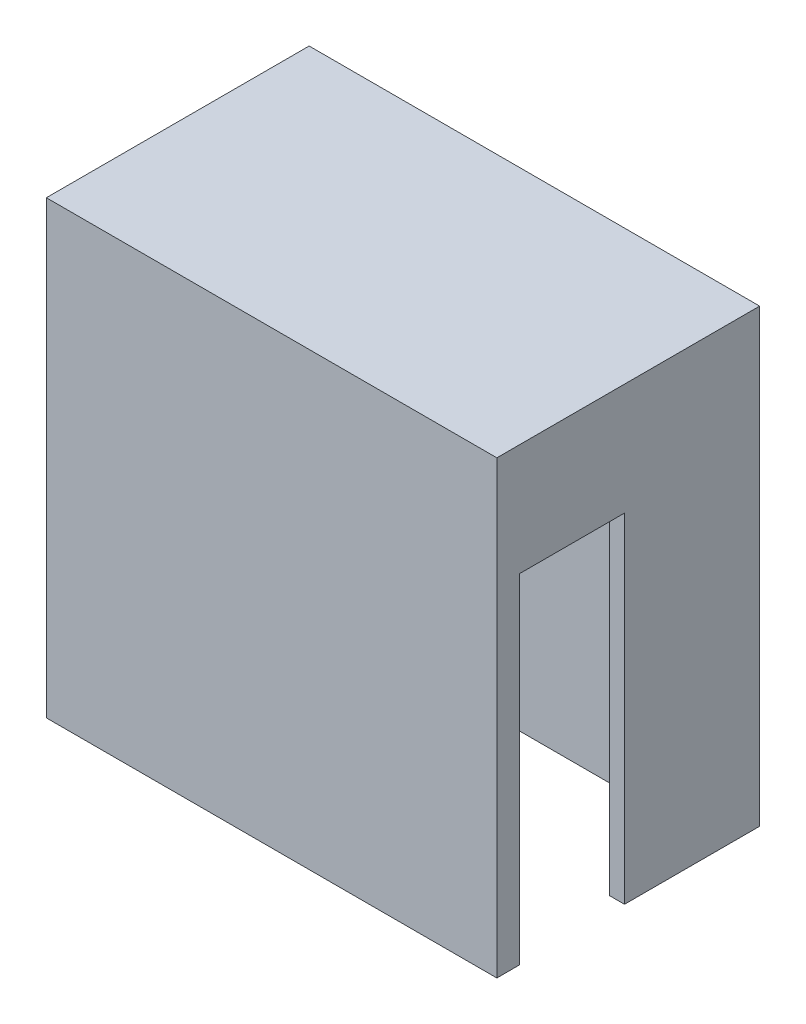
SolidWorks part; units mm, degrees
ref_plane "Front Plane" through (0, 0, 0) normal (0, 0, 1) x (1, 0, 0)
ref_plane "Top Plane" through (0, 0, 0) normal (0, 1, 0) x (1, 0, 0)
ref_plane "Right Plane" through (0, 0, 0) normal (1, 0, 0) x (0, 0, -1)
sketch "Sketch1" plane through (0, 0, 0) normal (0, 1, 0) x (1, 0, 0)
  line L1 (0, 0) -> (38.1, 0)
  line L2 (0, 0) -> (0, 22.225)
  line L3 (0, 22.225) -> (38.1, 22.225)
  line L4 (38.1, 0) -> (38.1, 22.225)
extrude "Boss-Extrude2" add sketch "Sketch1" along normal blind 38.1 contours L1 L4 L3 L2
sketch "Sketch3" plane through (0, 0, 0) normal (0, -1, 0) x (1, 0, 0)
  line L0 (0, -22.225) -> (1.27, -22.225)
  line L2 (0, -22.225) -> (38.1, -22.225) construction
  line L4 (1.27, -22.225) -> (1.27, -19.05)
  line L5 (38.1, 0) -> (36.83, 0)
  line L6 (0, 0) -> (38.1, 0) construction
  line L7 (36.83, 0) -> (36.83, -6.35)
  line L9 (1.27, -19.05) -> (36.83, -19.05)
  line L10 (1.27, -19.05) -> (1.27, -6.35)
  line L11 (1.27, -6.35) -> (36.83, -6.35)
  line L12 (36.83, -19.05) -> (36.83, -6.35)
sketch "Sketch4" plane through (0, 0, 0) normal (0, -1, 0) x (1, 0, 0)
  line L1 (1.27, -19.05) -> (36.83, -19.05)
  line L2 (1.27, -19.05) -> (1.27, -6.35)
  line L3 (1.27, -6.35) -> (36.83, -6.35)
  line L4 (36.83, -19.05) -> (36.83, -6.35)
  point P6 (31.75, -15.875)
extrude "Cut-Extrude1" cut sketch "Sketch4" against normal blind 31.75
sketch "Sketch5" plane through (0, 0, 0) normal (-1, 0, 0) x (0, 0, 1)
  line L21 (-1.9053, -0.5539) -> (-10.7953, -0.5539)
  line L22 (-1.9053, -0.5539) -> (-1.9053, 28.6561)
  line L23 (-1.9053, 28.6561) -> (-10.7953, 28.6561)
  line L24 (-10.7953, -0.5539) -> (-10.7953, 28.6561)
extrude "Cut-Extrude3" cut sketch "Sketch5" against normal through all contours L22 L21 L24 L23
